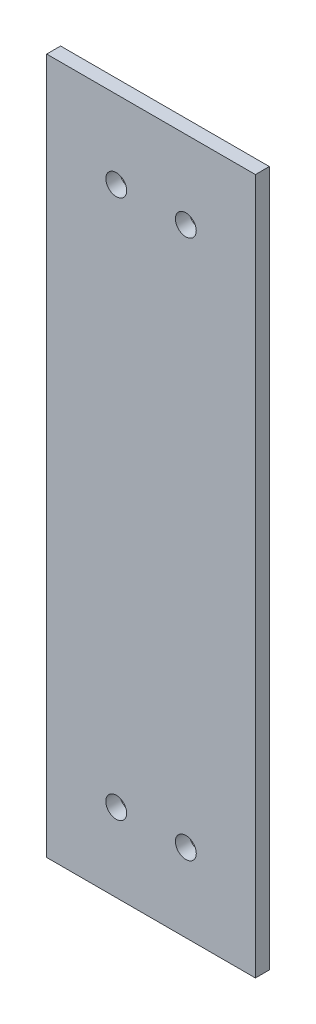
SolidWorks part; units mm, degrees
ref_plane "Спереди" through (0, 0, 0) normal (0, 0, 1) x (1, 0, 0)
ref_plane "Сверху" through (0, 0, 0) normal (0, 1, 0) x (1, 0, 0)
ref_plane "Справа" through (0, 0, 0) normal (1, 0, 0) x (0, 0, -1)
sketch "Эскиз1" plane through (0, 0, 0) normal (0, 0, 1) x (1, 0, 0)
  line L1 (0, 0) -> (30, 0)
  line L2 (0, 0) -> (0, 100)
  line L3 (0, 100) -> (30, 100)
  line L4 (30, 0) -> (30, 100)
  circle A0 centre (10, 11.25) radius 1.5
  circle A1 centre (20, 11.25) radius 1.5
  circle A2 centre (20, 88.75) radius 1.5
  circle A3 centre (10, 88.75) radius 1.5
  dimension "D3" = 3
  dimension "D1" = 100
  dimension "D2" = 30
  dimension "D4" = 11.25
  dimension "D5" = 10
  dimension "D8" = 11.25
  dimension "D9" = 10
  dimension "D10" = 10
  dimension "D7" = 2
  dimension "D6" = 2
extrude "Бобышка-Вытянуть1" add sketch "Эскиз1" along normal blind 2
